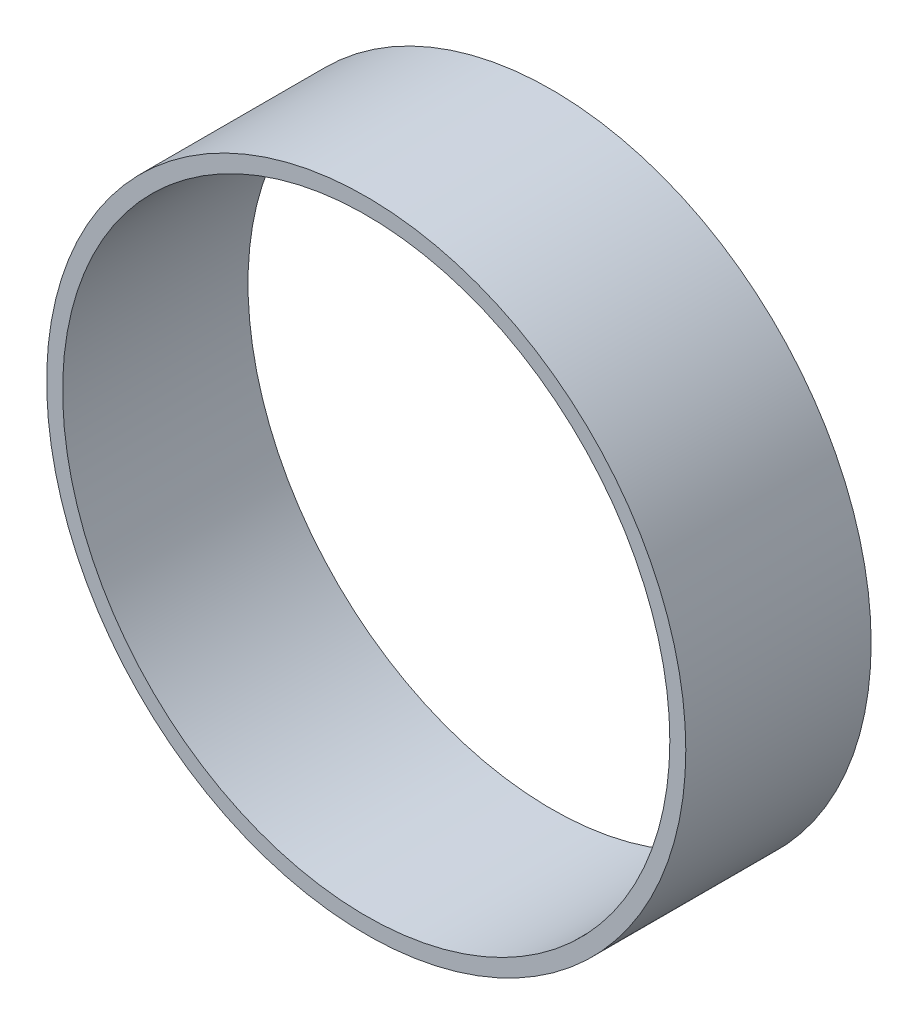
SolidWorks part; units mm, degrees
ref_plane "Front Plane" through (0, 0, 0) normal (0, 0, 1) x (1, 0, 0)
ref_plane "Top Plane" through (0, 0, 0) normal (0, 1, 0) x (1, 0, 0)
ref_plane "Right Plane" through (0, 0, 0) normal (1, 0, 0) x (0, 0, -1)
sketch "Sketch1" plane through (0, 0, 0) normal (0, 0, 1) x (1, 0, 0)
  circle A0 centre (-43.2127, 1.4419) radius 10
  dimension "D1" = 20
extrude "Boss-Extrude1" add sketch "Sketch1" along normal blind 5.8
sketch "Sketch2" plane through (0, 0, 5.8) normal (0, 0, 1) x (1, 0, 0)
  circle A0 centre (-43.2127, 1.4419) radius 9.5
  dimension "D1" = 19
extrude "Cut-Extrude1" cut sketch "Sketch2" against normal blind 5.8
